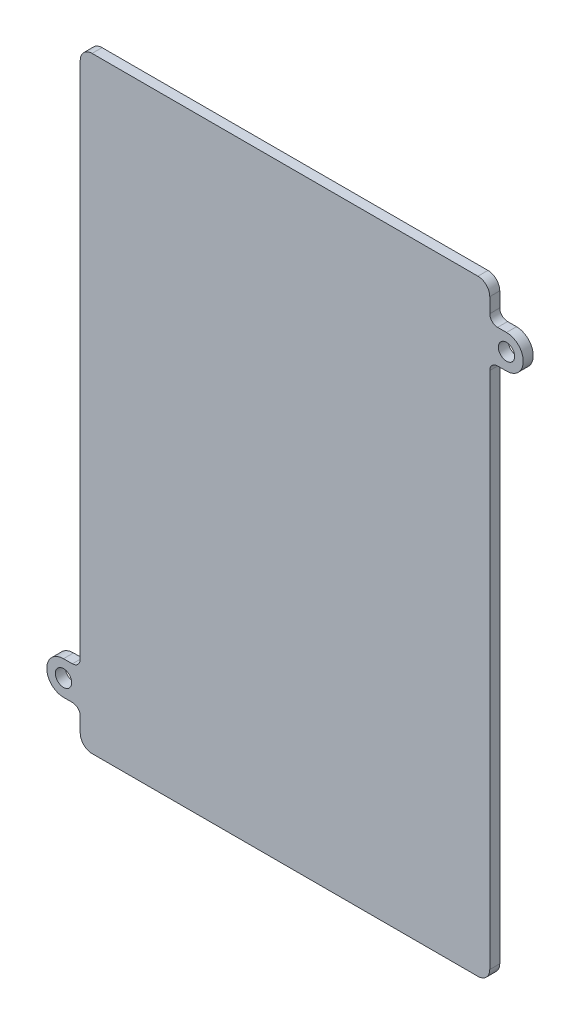
SolidWorks part; units mm, degrees
ref_plane "Front Plane" through (0, 0, 0) normal (0, 0, 1) x (1, 0, 0)
ref_plane "Top Plane" through (0, 0, 0) normal (0, 1, 0) x (1, 0, 0)
ref_plane "Right Plane" through (0, 0, 0) normal (1, 0, 0) x (0, 0, -1)
sketch "Sketch1" plane through (0, 0, 0) normal (0, 0, 1) x (1, 0, 0)
  line L20 (52, -74) -> (52, 59.75)
  line L21 (52, 59.75) -> (56.25, 59.75)
  line L22 (56.25, 68.25) -> (52, 68.25)
  line L23 (52, 68.25) -> (52, 74)
  line L24 (49, 77) -> (-49, 77)
  line L25 (-52, 74) -> (-52, -59.75)
  line L26 (-52, -59.75) -> (-56.25, -59.75)
  line L27 (-56.25, -68.25) -> (-52, -68.25)
  line L28 (-52, -68.25) -> (-52, -74)
  line L29 (-49, -77) -> (49, -77)
  arc A12 (56.25, 59.75) -> (56.25, 68.25) centre (56.25, 64) ccw
  arc A13 (52, 74) -> (49, 77) centre (49, 74) ccw
  arc A14 (-49, 77) -> (-52, 74) centre (-49, 74) ccw
  arc A15 (-56.25, -59.75) -> (-56.25, -68.25) centre (-56.25, -64) ccw
  arc A16 (-52, -74) -> (-49, -77) centre (-49, -74) ccw
  arc A17 (49, -77) -> (52, -74) centre (49, -74) ccw
extrude "Boss-Extrude1" add sketch "Sketch1" along normal blind 2.54
sketch "Sketch2" plane through (0, 0, 2.54) normal (0, 0, 1) x (1, 0, 0)
  circle A0 centre (56.25, 64) radius 2.075
  circle A1 centre (-56.25, -64) radius 2.075
extrude "Cut-Extrude1" cut sketch "Sketch2" against normal blind 10
fillet "Fillet1" radius 2 4 edges at (-52, -68.25, 1.27) (-52, -59.75, 1.27) (52, 68.25, 1.27) (52, 59.75, 1.27)
